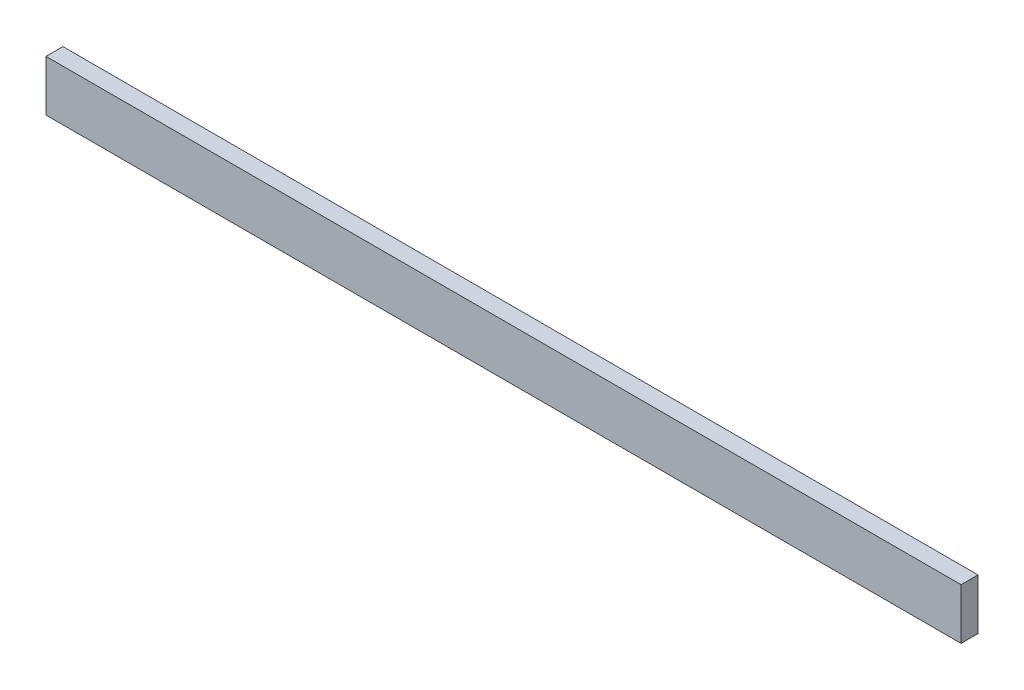
SolidWorks part; units mm, degrees
ref_plane "前视基准面" through (0, 0, 0) normal (0, 0, 1) x (1, 0, 0)
ref_plane "上视基准面" through (0, 0, 0) normal (0, 1, 0) x (1, 0, 0)
ref_plane "右视基准面" through (0, 0, 0) normal (1, 0, 0) x (0, 0, -1)
sketch "草图1" plane through (0, 0, 0) normal (0, 0, 1) x (1, 0, 0)
  line L0 (0, 0) -> (54, 0)
  line L1 (55, 0) -> (-55, 0) construction
  dimension "D1" = 54
extrude "拉伸-薄壁1" add sketch "草图1" along normal blind 1 thin
